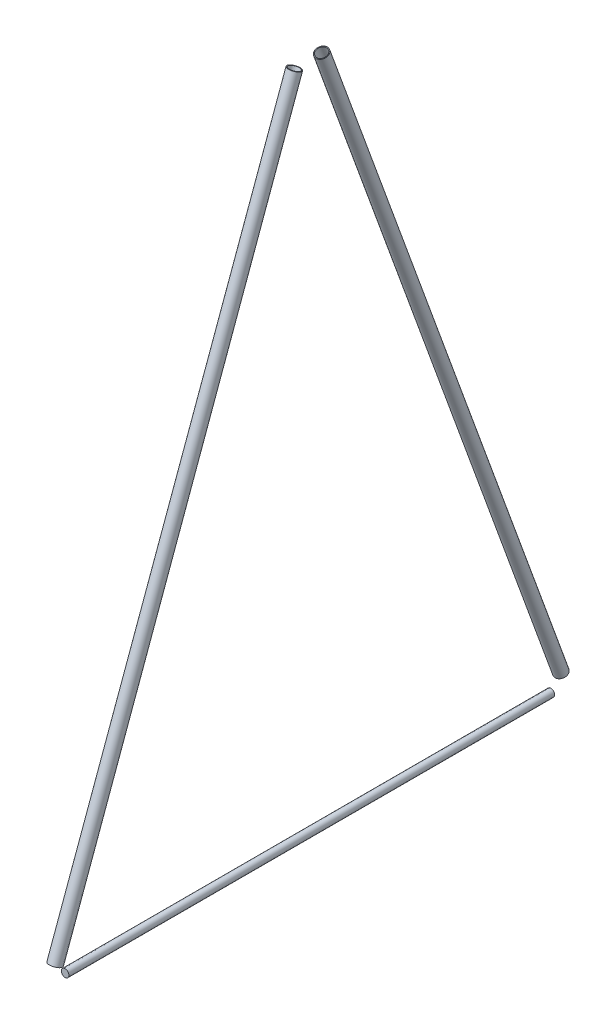
SolidWorks part; units mm, degrees
ref_plane "Front Plane" through (0, 0, 0) normal (0, 0, 1) x (1, 0, 0)
ref_plane "Top Plane" through (0, 0, 0) normal (0, 1, 0) x (1, 0, 0)
ref_plane "Right Plane" through (0, 0, 0) normal (1, 0, 0) x (0, 0, -1)
sketch "Sketch1" plane through (0, 0, 0) normal (1, 0, 0) x (0, 0, -1)
  line L0 (-508, 44.45) -> (508, 44.45)
  line L1 (528.8803, 71.1133) -> (28.575, 1443.2485)
  line L2 (-28.575, 1443.2485) -> (-528.8803, 71.1133)
  line L3 (-28.575, 1443.2485) -> (28.575, 1443.2485)
  line L4 (528.8803, 71.1133) -> (508, 63.5)
  line L5 (508, 63.5) -> (508, 44.45)
  line L6 (0, -134.9267) -> (0, -276.7949) construction
  point P1 (538.6023, 44.45)
  point P2 (0, 1521.6181)
  point P3 (0, 44.45)
  point P6 (0, 1443.2485)
  point P9 (-538.6023, 44.45)
  point P11 (278.7277, 757.1809)
  point P13 (-278.7277, 757.1809)
  dimension "D1" = 28.3804
  dimension "D2" = 30.6023
  dimension "D3" = 83.4166
  dimension "D4" = 57.15
  dimension "D5" = 1460.5
  dimension "D6" = 44.45
  dimension "D9" = 22.225
  dimension "D10" = 1016
  dimension "D11" = 69.967
  dimension "D12" = 19.05
sketch "Sketch2" plane through (0, 0, 0) normal (1, 0, 0) x (0, 0, -1)
  line L0 (514.35, 0) -> (514.35, 59.0564)
  line L1 (514.35, 59.0564) -> (548.953, 71.6733)
  line L2 (548.953, 71.6733) -> (546.7777, 77.6391)
  line L3 (546.7777, 77.6391) -> (508, 63.5)
  line L4 (514.35, 0) -> (508, 0)
  line L5 (508, 0) -> (508, 63.5)
  line L6 (528.8803, 71.1133) -> (28.575, 1443.2485) construction
  line L7 (-508, 44.45) -> (508, 44.45) construction
  dimension "D1" = 44.45
  dimension "D2" = 6.35
  dimension "D3" = 19.05
extrude "Boss-Extrude1" [suppressed] add sketch "Sketch2" along normal mid plane 76.2
sketch "Sketch3" [suppressed] plane through (0, 0, -514.35) normal (0, 0, -1) x (-1, 0, 0)
  circle A0 centre (0, 0) radius 26.162
  circle A1 centre (0, 44.45) radius 3.9751
  dimension "D1" = 52.324
  dimension "D2" = 7.9502
extrude "Cut-Extrude1" [suppressed] cut sketch "Sketch3" against normal up to next
sketch "Sketch4" [suppressed] plane through (0, -114.9643, -42.3941) normal (0, -0.9382, -0.346) x (1, 0, 0)
  circle A0 centre (0, -520.8211) radius 3.9751
  dimension "D1" = 7.9502
extrude "Cut-Extrude2" [suppressed] cut sketch "Sketch4" against normal blind 25.4
sketch "Sketch5" plane through (0, 0, 0) normal (1, 0, 0) x (0, 0, -1)
  line L0 (43.4895, 1448.6866) -> (9.525, 1436.3025)
  line L4 (8.4035, 1442.6525) -> (41.3143, 1454.6524)
  line L5 (41.3143, 1454.6524) -> (43.4895, 1448.6866)
  line L6 (528.8803, 71.1133) -> (28.575, 1443.2485) construction
  line L7 (-9.525, 1436.3025) -> (-43.4895, 1448.6866)
  line L8 (-43.4895, 1448.6866) -> (-41.3143, 1454.6524)
  line L9 (-41.3143, 1454.6524) -> (-8.4035, 1442.6525)
  line L10 (-8.4035, 1442.6525) -> (8.4035, 1442.6525)
  line L11 (-9.525, 1436.3025) -> (9.525, 1436.3025)
  line L12 (-28.575, 1443.2485) -> (-528.8803, 71.1133) construction
  dimension "D1" = 6.35
  dimension "D2" = 19.05
  dimension "D3" = 15.875
  dimension "D4" = 6.35
  dimension "D6" = 6.35
  dimension "D7" = 15.875
extrude "Boss-Extrude2" [suppressed] add sketch "Sketch5" along normal mid plane 44.45 separate body
ref_plane "Plane1" through (0, 757.1809, -278.7277) normal (0, 0.9395, 0.3426) x (1, 0, 0)
sketch "Sketch6" plane through (0, 757.1809, -278.7277) normal (0, 0.9395, 0.3426) x (1, 0, 0)
  circle A0 centre (0, 0) radius 12.7
  circle A1 centre (0, 0) radius 11.049
  dimension "D1" = 25.4
  dimension "D2" = 1.651
extrude "Boss-Extrude3" add sketch "Sketch6" against normal up to vertex (730.25 mm away) and the other way up to vertex (730.25 mm away) separate body up to point (0, 71.1133, -528.8803) other way up to point (0, 1443.2485, -28.575)
ref_plane "Plane2" through (0, 757.1809, 278.7277) normal (0, -0.9395, 0.3426) x (-1, 0, 0)
sketch "Sketch7" plane through (0, 757.1809, 278.7277) normal (0, -0.9395, 0.3426) x (-1, 0, 0)
  circle A0 centre (0, 0) radius 12.7
  circle A1 centre (0, 0) radius 11.049
  dimension "D1" = 1.651
  dimension "D2" = 25.4
extrude "Boss-Extrude4" add sketch "Sketch7" against normal up to vertex (730.25 mm away) and the other way up to vertex (730.25 mm away) separate body up to point (0, 1443.2485, 28.575) other way up to point (0, 71.1133, 528.8803)
sketch "Sketch8" plane through (0, 0, 0) normal (1, 0, 0) x (0, 0, -1)
  line L0 (-508, 63.5) -> (-508, -6.35)
  line L1 (-508, -6.35) -> (-514.35, -6.35)
  line L2 (-514.35, -6.35) -> (-514.35, 59.0564)
  line L3 (-514.35, 59.0564) -> (-548.953, 71.6733)
  line L4 (-548.953, 71.6733) -> (-546.7777, 77.6391)
  line L5 (-546.7777, 77.6391) -> (-508, 63.5)
  line L6 (-28.575, 1443.2485) -> (-528.8803, 71.1133) construction
  dimension "D1" = 6.35
  dimension "D2" = 19.05
  dimension "D3" = 50.8
extrude "Boss-Extrude5" [suppressed] add sketch "Sketch8" along normal mid plane 76.2
sketch "Sketch9" [suppressed] plane through (0, 0, 514.35) normal (0, 0, 1) x (1, 0, 0)
  circle A0 centre (0, 0) radius 26.162
  circle A1 centre (0, 44.45) radius 3.9751
  dimension "D1" = 52.324
  dimension "D2" = 7.9502
extrude "Cut-Extrude3" [suppressed] cut sketch "Sketch9" against normal blind 25.4
sketch "Sketch10" plane through (0, 0, 0) normal (0, 0, 1) x (1, 0, 0)
  circle A0 centre (0, 44.45) radius 7.9375
  circle A1 centre (0, 44.45) radius 6.2865 construction
  dimension "D1" = 1.651
  dimension "D2" = 15.875
extrude "Boss-Extrude6" add sketch "Sketch10" against normal up to vertex (508 mm away) and the other way up to vertex (508 mm away) separate body up to point (0, 44.45, -508) other way up to point (0, 44.45, 508)
